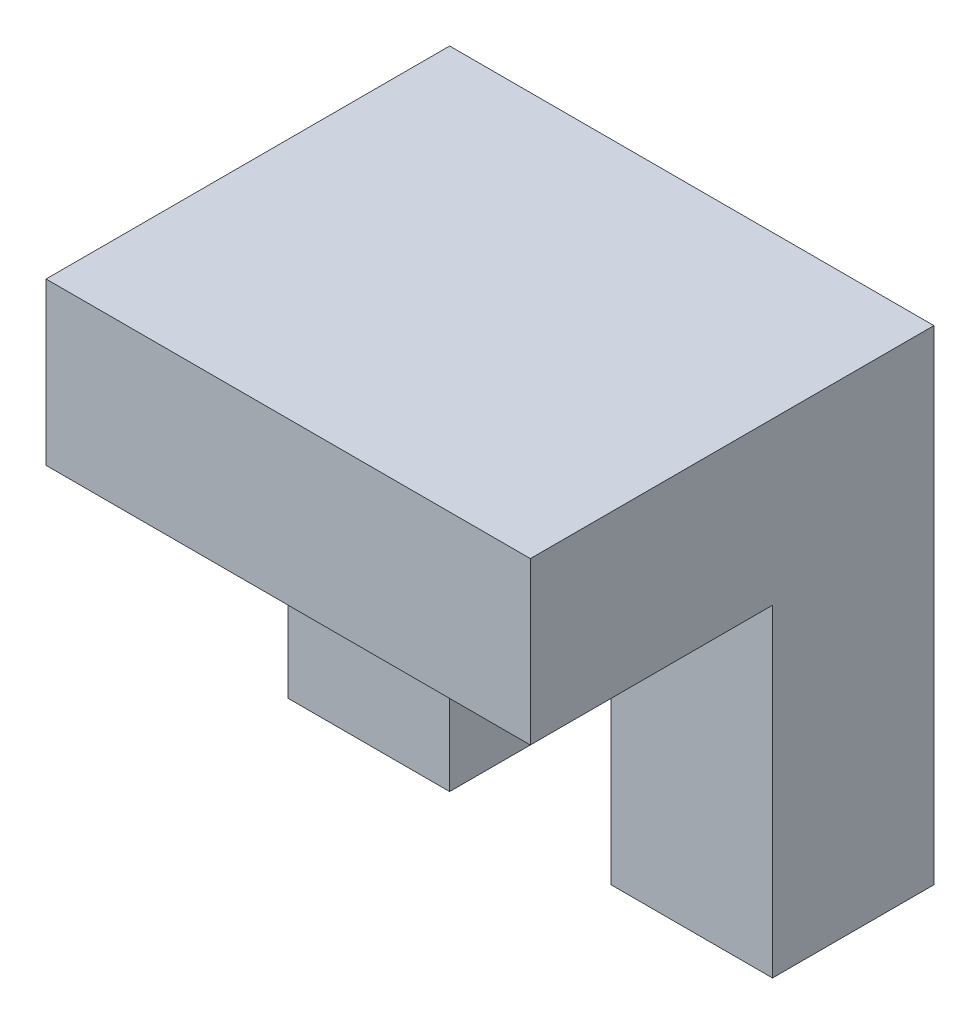
SolidWorks part; units mm, degrees
ref_plane "Plano frontal" through (0, 0, 0) normal (0, 0, 1) x (1, 0, 0)
ref_plane "Plano superior" through (0, 0, 0) normal (0, 1, 0) x (1, 0, 0)
ref_plane "Plano direito" through (0, 0, 0) normal (1, 0, 0) x (0, 0, -1)
sketch "Esboço1" plane through (0, 0, 0) normal (0, 0, 1) x (1, 0, 0)
  line L1 (0, 0) -> (60, 0)
  line L2 (0, 0) -> (0, 40)
  line L3 (0, 40) -> (60, 40)
  line L4 (60, 0) -> (60, 40)
  dimension "D1" = 60
  dimension "D2" = 40
extrude "Ressalto-extrusão1" add sketch "Esboço1" along normal blind 20
sketch "Esboço8" plane through (0, 0, 20) normal (0, 0, 1) x (1, 0, 0)
  line L0 (0, 0) -> (60, 0) construction
  line L4 (20, 0) -> (20, 20)
  line L5 (20, 20) -> (40, 20)
  line L7 (20, 0) -> (40, 0)
  line L8 (40, 20) -> (40, 0)
extrude "Corte-extrusão2" cut sketch "Esboço8" against normal blind 40
sketch "Esboço9" plane through (0, 40, 0) normal (0, 1, 0) x (1, 0, 0)
  line L1 (60, 0) -> (0, 0)
  line L2 (60, 0) -> (60, -50)
  line L3 (60, -50) -> (0, -50)
  line L4 (0, 0) -> (0, -50)
  dimension "D1" = 60
  dimension "D2" = 50
extrude "Ressalto-extrusão2" add sketch "Esboço9" along normal blind 20
